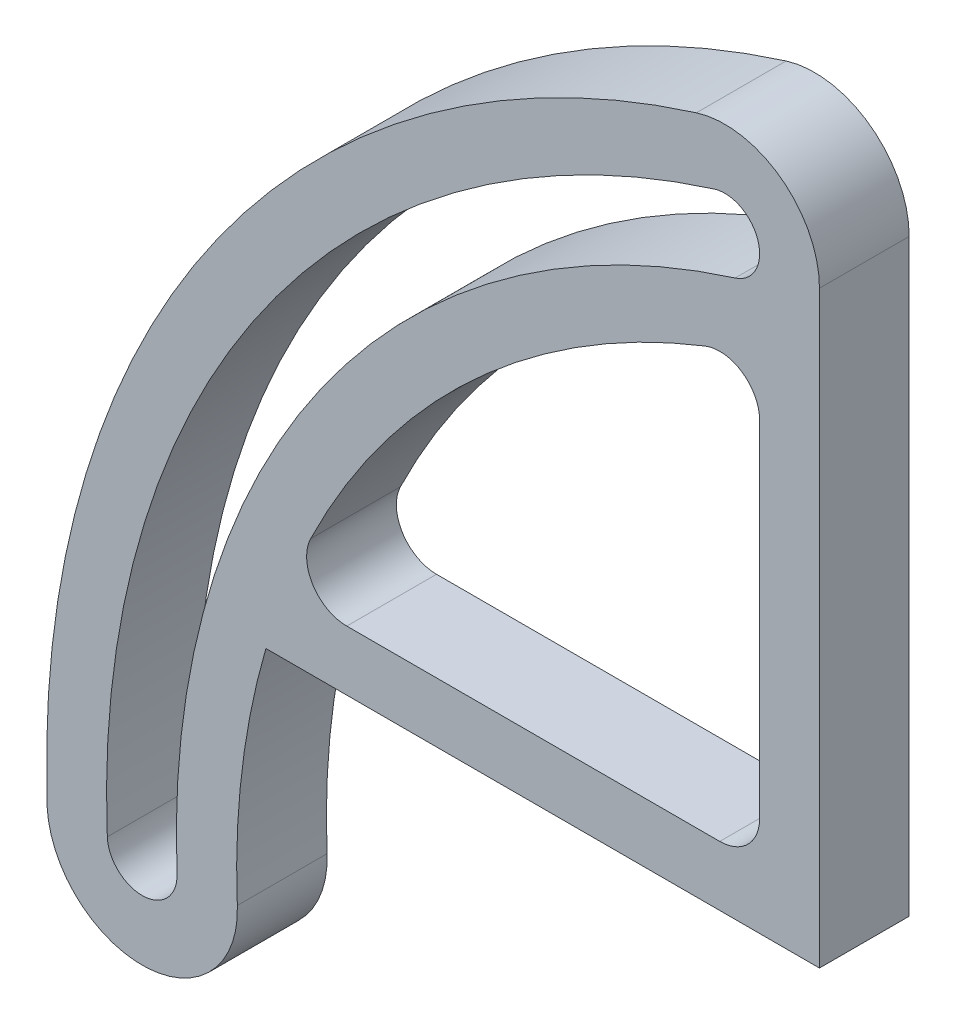
SolidWorks part; units mm, degrees
ref_plane "Front Plane" through (0, 0, 0) normal (0, 0, 1) x (1, 0, 0)
ref_plane "Top Plane" through (0, 0, 0) normal (0, 1, 0) x (1, 0, 0)
ref_plane "Right Plane" through (0, 0, 0) normal (1, 0, 0) x (0, 0, -1)
sketch "Sketch1" plane through (0, 0, 0) normal (0, 0, 1) x (1, 0, 0)
  line L6 (-2.6367, -1.1494) -> (25.122, -1.1494)
  line L8 (25.122, 28.3749) -> (25.122, -1.1494)
  line L13 (1.4191, 1.8506) -> (20.122, 1.8506)
  line L15 (22.122, 28.3749) -> (22.122, -1.1494) construction
  line L19 (22.122, 21.1353) -> (22.122, 3.8506)
  line L20 (-2.0705, 1.8506) -> (25.122, 1.8506) construction
  line L22 (-2.0705, -1.1494) -> (25.122, -1.1494) construction
  arc A6 (-8.8405, -13.2307) -> (20.372, 28.3749) centre (32.869, -11.4578) cw construction
  arc A7 (19.8481, 30.0447) -> (-10.5889, -13.305) centre (32.869, -11.4578) ccw
  arc A8 (20.8958, 26.7052) -> (-7.092, -13.1564) centre (32.869, -11.4578) ccw
  arc A9 (20.8958, 26.7052) -> (19.8481, 30.0447) centre (20.372, 28.3749) ccw
  arc A10 (-10.5889, -13.305) -> (-7.092, -13.1564) centre (-8.8405, -13.2307) ccw
  arc A11 (18.95, 32.9071) -> (-13.6053, -12.9145) centre (32.869, -11.4578) ccw
  arc A15 (-13.5862, -13.4324) -> (-4.0947, -13.029) centre (-8.8405, -13.2307) ccw construction
  arc A16 (21.7939, 23.8428) -> (-4.0947, -13.029) centre (32.869, -11.4578) ccw construction
  arc A17 (21.7939, 23.8428) -> (18.95, 32.9071) centre (20.372, 28.3749) ccw construction
  arc A18 (18.95, 32.9071) -> (25.122, 28.3749) centre (20.372, 28.3749) cw
  arc A24 (-0.391, 4.7459) -> (1.4191, 1.8506) centre (1.4191, 3.8641) ccw
  arc A28 (19.3935, 22.9979) -> (-0.391, 4.7459) centre (32.869, -11.4578) ccw
  arc A31 (18.95, 32.9071) -> (-13.5862, -13.4324) centre (32.869, -11.4578) ccw construction
  arc A34 (22.122, 3.8506) -> (20.122, 1.8506) centre (20.122, 3.8506) cw
  arc A36 (22.122, 21.1353) -> (19.3935, 22.9979) centre (20.122, 21.1353) ccw
  arc A41 (-2.6367, -1.1494) -> (-4.0695, -13.0279) centre (32.869, -11.4578) ccw
  arc A43 (-13.6053, -12.9145) -> (-4.0695, -13.0279) centre (-8.8405, -13.2307) ccw
  point P20 (-1.2974, 12.5313)
  dimension "D3" = 3
  dimension "D2" = 2
  dimension "D1" = 3
  dimension "D6" = 2
  dimension "D8" = 3
  dimension "D4" = 3
extrude "Boss-Extrude1" add sketch "Sketch1" along normal blind 4.5 contours L8 L6 A41 A43 A11 A18 | L19 A34 L13 A24 A28 A36 | A8 A10 A7 A9
